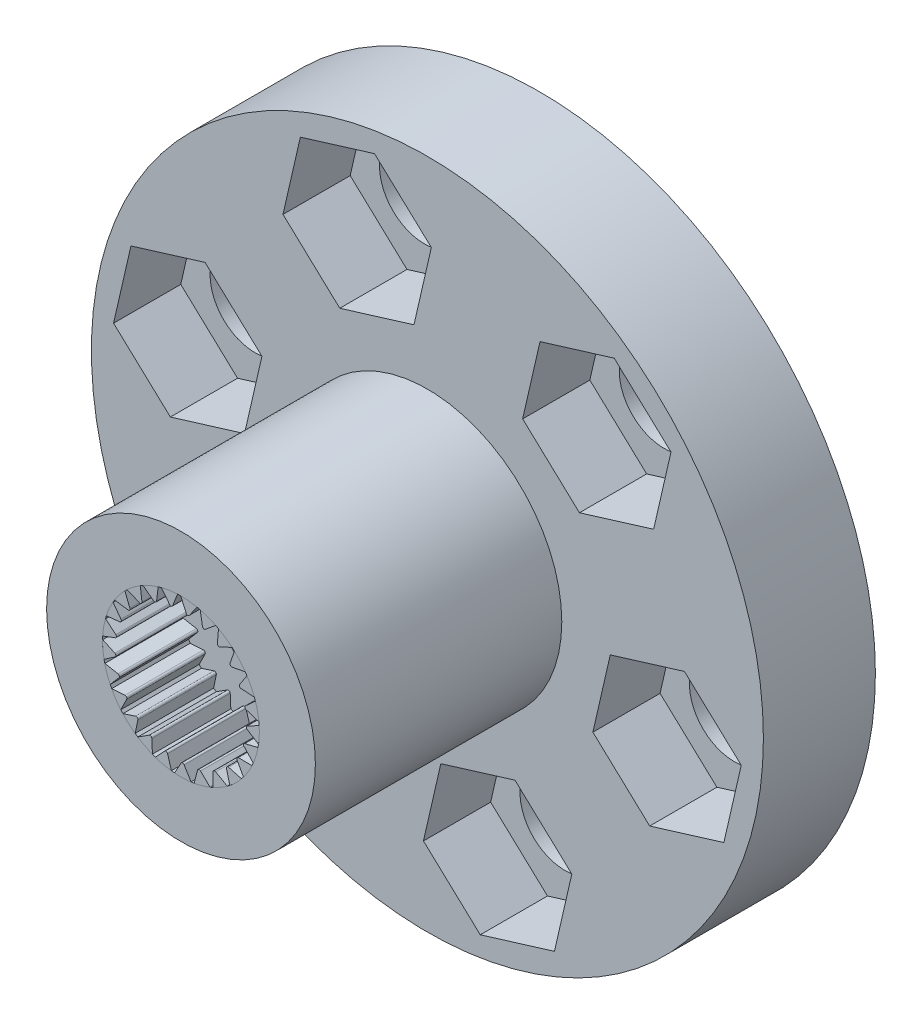
SolidWorks part; units mm, degrees
ref_plane "前视基准面" through (0, 0, 0) normal (0, 0, 1) x (1, 0, 0)
ref_plane "上视基准面" through (0, 0, 0) normal (0, 1, 0) x (1, 0, 0)
ref_plane "右视基准面" through (0, 0, 0) normal (1, 0, 0) x (0, 0, -1)
other "Configuration Table"
sketch "草图1" plane through (0, 0, 0) normal (0, 0, 1) x (1, 0, 0)
  circle A0 centre (-15, -33.75) radius 15
  dimension "D1" = 30
extrude "凸台-拉伸1" add sketch "草图1" along normal blind 5
sketch "草图2" plane through (0, 0, 5) normal (0, 0, 1) x (1, 0, 0)
  circle A0 centre (-18.1356, -23.2064) radius 2
  circle A1 centre (-15, -33.75) radius 11 construction
  circle A2 centre (-7.4367, -25.7627) radius 2
  circle A3 centre (-4.3012, -36.3063) radius 2
  circle A4 centre (-11.8644, -44.2936) radius 2
  circle A5 centre (-22.5633, -41.7373) radius 2
  circle A6 centre (-25.6988, -31.1937) radius 2
  point P17 (-15, -33.75)
  dimension "D1" = 22
  dimension "D2" = 4
  dimension "D3" = 6
extrude "切除-拉伸1" cut sketch "草图2" against normal through all
sketch "草图3" plane through (0, 0, 5) normal (0, 0, 1) x (1, 0, 0)
  circle A0 centre (-15, -33.75) radius 6
  circle A1 centre (-15, -33.75) radius 3.5
  dimension "D1" = 12
  dimension "D2" = 7
extrude "凸台-拉伸2" add sketch "草图3" along normal blind 11
sketch "草图4" plane through (0, 0, 5) normal (0, 0, 1) x (1, 0, 0)
  circle A0 centre (-15, -33.75) radius 3.5 construction
  circle A1 centre (-15, -33.75) radius 3.5
extrude "凸台-拉伸3" add sketch "草图4" along normal blind 7.5
sketch "草图5" plane through (0, 0, 0) normal (0, 0, -1) x (-1, 0, 0)
  circle A0 centre (15, -33.75) radius 4
  dimension "D1" = 8
extrude "切除-拉伸2" cut sketch "草图5" against normal blind 10
sketch "草图6" plane through (0, 0, 10) normal (0, 0, -1) x (-1, 0, 0)
  circle A0 centre (15, -33.75) radius 1.5
  dimension "D1" = 3
extrude "切除-拉伸3" cut sketch "草图6" against normal blind 8
sketch "草图8" plane through (0, 0, 5) normal (0, 0, 1) x (1, 0, 0)
  line L0 (-4.1251, -24.7462) -> (-6.6612, -22.3865)
  line L7 (-17.3601, -19.8302) -> (-20.6717, -20.8467)
  line L8 (-20.6717, -20.8467) -> (-21.4472, -24.2229)
  line L9 (-21.4472, -24.2229) -> (-18.9111, -26.5825)
  line L10 (-18.9111, -26.5825) -> (-15.5994, -25.5661)
  line L11 (-15.5994, -25.5661) -> (-14.824, -22.1899)
  line L12 (-14.824, -22.1899) -> (-17.3601, -19.8302)
  line L13 (-6.6612, -22.3865) -> (-9.9728, -23.403)
  line L14 (-9.9728, -23.403) -> (-10.7483, -26.7792)
  line L15 (-10.7483, -26.7792) -> (-8.2122, -29.1389)
  line L16 (-8.2122, -29.1389) -> (-4.9006, -28.1224)
  line L17 (-4.9006, -28.1224) -> (-4.1251, -24.7462)
  line L18 (-1.7651, -38.666) -> (-0.9896, -35.2898)
  line L19 (-0.9896, -35.2898) -> (-3.5257, -32.9302)
  line L20 (-3.5257, -32.9302) -> (-6.8373, -33.9467)
  line L21 (-6.8373, -33.9467) -> (-7.6128, -37.3228)
  line L22 (-7.6128, -37.3228) -> (-5.0767, -39.6825)
  line L23 (-5.0767, -39.6825) -> (-1.7651, -38.666)
  line L24 (-12.6399, -47.6698) -> (-9.3283, -46.6533)
  line L25 (-9.3283, -46.6533) -> (-8.5528, -43.2771)
  line L26 (-8.5528, -43.2771) -> (-11.0889, -40.9175)
  line L27 (-11.0889, -40.9175) -> (-14.4006, -41.9339)
  line L28 (-14.4006, -41.9339) -> (-15.176, -45.3101)
  line L29 (-15.176, -45.3101) -> (-12.6399, -47.6698)
  line L30 (-25.8749, -42.7538) -> (-23.3388, -45.1135)
  line L31 (-23.3388, -45.1135) -> (-20.0272, -44.097)
  line L32 (-20.0272, -44.097) -> (-19.2517, -40.7208)
  line L33 (-19.2517, -40.7208) -> (-21.7878, -38.3611)
  line L34 (-21.7878, -38.3611) -> (-25.0994, -39.3776)
  line L35 (-25.0994, -39.3776) -> (-25.8749, -42.7538)
  line L36 (-28.2349, -28.834) -> (-29.0104, -32.2102)
  line L37 (-29.0104, -32.2102) -> (-26.4743, -34.5698)
  line L38 (-26.4743, -34.5698) -> (-23.1627, -33.5533)
  line L39 (-23.1627, -33.5533) -> (-22.3872, -30.1772)
  line L40 (-22.3872, -30.1772) -> (-24.9233, -27.8175)
  line L41 (-24.9233, -27.8175) -> (-28.2349, -28.834)
  circle A6 centre (-18.1356, -23.2064) radius 3 construction
  point P16 (-15, -33.75)
  point P44 (-15, -33.75)
  dimension "D1" = 6
  dimension "D2" = 6
extrude "切除-拉伸4" cut sketch "草图8" against normal blind 3
sketch "草图9" plane through (0, 0, 16) normal (0, 0, 1) x (1, 0, 0)
  line L2 (-15.3724, -30.8127) -> (-15.1528, -30.2533)
  line L3 (-15.5094, -30.8333) -> (-15.884, -30.3635)
  line L5 (-15, -33.75) -> (-16.3657, -30.5274) construction
  line L6 (-16.2187, -31.0517) -> (-16.6985, -30.6897)
  line L7 (-16.0912, -30.9976) -> (-16.0176, -30.4012)
  line L8 (-14.6302, -30.8124) -> (-14.2784, -30.3252)
  line L9 (-14.7681, -30.7983) -> (-15.0141, -30.25)
  line L10 (-13.9113, -30.9966) -> (-13.4494, -30.6122)
  line L11 (-14.0413, -30.9487) -> (-14.1432, -30.3565)
  line L12 (-13.2607, -31.3539) -> (-12.7178, -31.0964)
  line L13 (-13.3748, -31.2751) -> (-13.3262, -30.6762)
  line L14 (-12.7195, -31.8617) -> (-12.1295, -31.7474)
  line L15 (-12.8103, -31.7571) -> (-12.6144, -31.189)
  line L16 (-12.3215, -32.4882) -> (-11.7217, -32.5242)
  line L17 (-12.3835, -32.3642) -> (-12.0524, -31.8627)
  line L18 (-12.0919, -33.1939) -> (-11.5198, -33.3779)
  line L19 (-12.1211, -33.0585) -> (-11.6757, -32.6551)
  line L20 (-12.0449, -33.9346) -> (-11.5366, -34.2551)
  line L21 (-12.0395, -33.7961) -> (-11.5078, -33.5162)
  line L22 (-12.1837, -34.6637) -> (-11.7711, -35.1006)
  line L23 (-12.144, -34.5309) -> (-11.5594, -34.392)
  line L24 (-12.4994, -35.3354) -> (-12.2084, -35.8611)
  line L25 (-12.428, -35.2166) -> (-11.8271, -35.2275)
  line L26 (-12.9722, -35.9074) -> (-12.8211, -36.489)
  line L27 (-12.8735, -35.8102) -> (-12.2943, -35.9701)
  line L28 (-13.5725, -36.3439) -> (-13.5707, -36.9449)
  line L29 (-13.4527, -36.2743) -> (-12.9314, -36.5733)
  line L30 (-14.2624, -36.6175) -> (-14.4102, -37.1999)
  line L31 (-14.1291, -36.5798) -> (-13.6985, -36.999)
  line L32 (-14.9987, -36.7108) -> (-15.2867, -37.2382)
  line L33 (-14.8602, -36.7075) -> (-14.5474, -37.2206)
  line L34 (-15.7351, -36.6181) -> (-16.1451, -37.0574)
  line L35 (-15.6001, -36.6494) -> (-15.4247, -37.2241)
  line L36 (-16.4252, -36.3452) -> (-16.9317, -36.6687)
  line L37 (-16.3022, -36.4091) -> (-16.2753, -37.0094)
  line L38 (-17.0259, -35.9092) -> (-17.5968, -36.0966)
  line L39 (-16.9226, -36.0017) -> (-17.0458, -36.5898)
  line L40 (-17.4992, -35.3376) -> (-18.0988, -35.3771)
  line L41 (-17.4222, -35.4528) -> (-17.6878, -35.9918)
  line L42 (-17.8155, -34.6662) -> (-18.4061, -34.5553)
  line L43 (-17.7695, -34.7969) -> (-18.1609, -35.2529)
  line L44 (-17.9549, -33.9372) -> (-18.4994, -33.6829)
  line L45 (-17.9429, -34.0753) -> (-18.4353, -34.4197)
  line L46 (-17.9086, -33.1965) -> (-18.3727, -32.8148)
  line L47 (-17.9313, -33.3332) -> (-18.4939, -33.5443)
  line L48 (-17.6796, -32.4905) -> (-18.0342, -32.0054)
  line L49 (-17.7356, -32.6173) -> (-18.333, -32.6818)
  line L50 (-17.2822, -31.8637) -> (-17.505, -31.3056)
  line L51 (-17.3679, -31.9726) -> (-17.9627, -31.8865)
  line L52 (-16.7414, -31.3554) -> (-16.8184, -30.7595)
  line L53 (-16.8515, -31.4395) -> (-17.4062, -31.2083)
  arc A0 (-16.0912, -30.9976) -> (-16.2187, -31.0517) centre (-16.1706, -30.9878) cw
  arc A1 (-15.3724, -30.8127) -> (-15.5094, -30.8333) centre (-15.4469, -30.7835) cw
  circle A6 centre (-15, -33.75) radius 3.5 construction
  arc A9 (-14.6302, -30.8124) -> (-14.7681, -30.7983) centre (-14.6951, -30.7655) cw
  arc A10 (-13.9113, -30.9966) -> (-14.0413, -30.9487) centre (-13.9624, -30.9351) cw
  arc A11 (-13.2607, -31.3539) -> (-13.3748, -31.2751) centre (-13.295, -31.2816) cw
  arc A12 (-12.7195, -31.8617) -> (-12.8103, -31.7571) centre (-12.7347, -31.7832) cw
  arc A13 (-12.3215, -32.4882) -> (-12.3835, -32.3642) centre (-12.3167, -32.4083) cw
  arc A14 (-12.0919, -33.1939) -> (-12.1211, -33.0585) centre (-12.0674, -33.1178) cw
  arc A15 (-12.0449, -33.9346) -> (-12.0395, -33.7961) centre (-12.0023, -33.8669) cw
  arc A16 (-12.1837, -34.6637) -> (-12.144, -34.5309) centre (-12.1255, -34.6088) cw
  arc A17 (-12.4994, -35.3354) -> (-12.428, -35.2166) centre (-12.4294, -35.2966) cw
  arc A18 (-12.9722, -35.9074) -> (-12.8735, -35.8102) centre (-12.8948, -35.8873) cw
  arc A19 (-13.5725, -36.3439) -> (-13.4527, -36.2743) centre (-13.4925, -36.3437) cw
  arc A20 (-14.2624, -36.6175) -> (-14.1291, -36.5798) centre (-14.1849, -36.6371) cw
  arc A21 (-14.9987, -36.7108) -> (-14.8602, -36.7075) centre (-14.9285, -36.7491) cw
  arc A22 (-15.7351, -36.6181) -> (-15.6001, -36.6494) centre (-15.6766, -36.6727) cw
  arc A23 (-16.4252, -36.3452) -> (-16.3022, -36.4091) centre (-16.3822, -36.4126) cw
  arc A24 (-17.0259, -35.9092) -> (-16.9226, -36.0017) centre (-17.0009, -35.9852) cw
  arc A25 (-17.4992, -35.3376) -> (-17.4222, -35.4528) centre (-17.4939, -35.4174) cw
  arc A26 (-17.8155, -34.6662) -> (-17.7695, -34.7969) centre (-17.8303, -34.7448) cw
  arc A27 (-17.9549, -33.9372) -> (-17.9429, -34.0753) centre (-17.9887, -34.0097) cw
  arc A28 (-17.9086, -33.1965) -> (-17.9313, -33.3332) centre (-17.9594, -33.2583) cw
  arc A29 (-17.6796, -32.4905) -> (-17.7356, -32.6173) centre (-17.7442, -32.5377) cw
  arc A30 (-17.2822, -31.8637) -> (-17.3679, -31.9726) centre (-17.3565, -31.8934) cw
  arc A31 (-16.7414, -31.3554) -> (-16.8515, -31.4395) centre (-16.8207, -31.3657) cw
  point P4 (-16.1081, -31.1351)
  point P132 (-15, -33.75)
  circle M4 centre (-15, -33.75) radius 3.5
  dimension "D1" = 30
  dimension "D3" = 0.08
  dimension "D2" = 0.66
  dimension "D4" = 25
extrude "凸台-拉伸4" add sketch "草图9" against normal up to next (3.5 mm away) separate body contours A28 L46 L47 M4 | A27 L44 L45 M4 | A26 L42 L43 M4 | A25 L40 L41 M4 | A24 L38 L39 M4 | A23 L36 L37 M4 | A22 L34 L35 M4 | A21 L32 L33 M4 | A20 L30 L31 M4 | A19 L28 L29 M4 | A18 L26 L27 M4 | A29 L48 L49 M4 | A30 L50 L51 M4 | A31 L52 L53 M4 | L5 A0 L7 M4 | A0 L5 L6 M4 | A1 L2 L3 M4 | A9 L8 L9 M4 | A10 L10 L11 M4 | A11 L12 L13 M4 | A12 L14 L15 M4 | A13 L16 L17 M4 | A14 L18 L19 M4 | A15 L20 L21 M4 | A16 L22 L23 M4 | A17 L24 L25 M4
